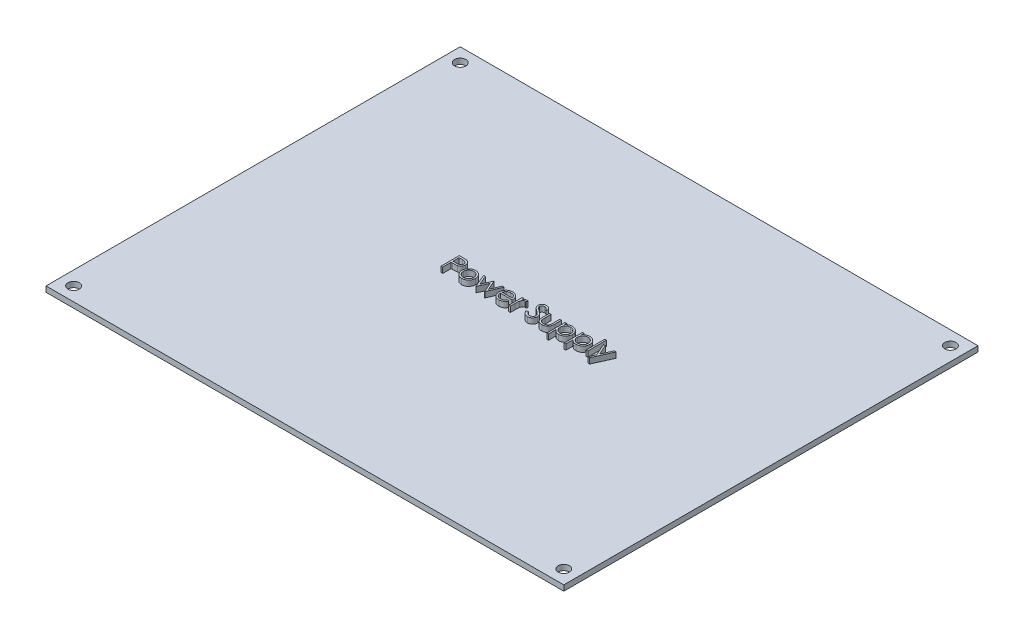
SolidWorks part; units mm, degrees
ref_plane "Front Plane" through (0, 0, 0) normal (0, 0, 1) x (1, 0, 0)
ref_plane "Top Plane" through (0, 0, 0) normal (0, 1, 0) x (1, 0, 0)
ref_plane "Right Plane" through (0, 0, 0) normal (1, 0, 0) x (0, 0, -1)
sketch "Sketch1" plane through (0, 0, 0) normal (0, 1, 0) x (1, 0, 0)
  line L1 (75, -60) -> (-75, -60)
  line L2 (75, -60) -> (75, 60)
  line L3 (75, 60) -> (-75, 60)
  line L4 (-75, -60) -> (-75, 60)
  line L5 (75, -60) -> (-75, 60) construction
  line L6 (75, 60) -> (-75, -60) construction
  point P0 (0, 0)
  dimension "D1" = 120
  dimension "D2" = 150
extrude "Boss-Extrude1" add sketch "Sketch1" along normal blind 1.6
hole_wizard "#4 Clearance Hole2" positions "Sketch4" profile "Sketch5" hole size "#4" standard "ANSI Inch" end condition through all
sketch "Sketch4" plane through (0, 1.6, 0) normal (0, 1, 0) x (1, 0, 0)
  line L0 (75, 60) -> (-75, 60) construction
  line L1 (-75, 60) -> (-75, -60) construction
  line L2 (75, -60) -> (75, 60) construction
  line L3 (-75, -60) -> (75, -60) construction
  point P0 (-71, 56)
  point P2 (71, 56)
  point P4 (71, -56)
  point P6 (-71, -56)
  point P19 (70.9175, 58.4005)
  point P20 (0, 0)
  point P21 (0, 0)
  dimension "D1" = 4
  dimension "D2" = 4
  dimension "D3" = 4
  dimension "D4" = 4
  dimension "D5" = 4
  dimension "D6" = 4
  dimension "D7" = 4
  dimension "D8" = 4
sketch "Sketch5" plane through (-71, 1.6, -56) normal (1, 0, 0) x (0, 0, 1)
  line L0 (0, 0) -> (0, 1.6)
  line L1 (0, 1.6) -> (1.6319, 1.6)
  line L2 (1.6319, 1.6) -> (1.6319, 0)
  line L5 (1.6319, 0) -> (0, 0)
  line L11 (0, -6.35) -> (0, 107.95) construction
  dimension "Thru Hole Dia." = 3.2639
  dimension "Thru Hole Depth" = 1.6
sketch "Sketch6" plane through (0, 1.6, 0) normal (0, 1, 0) x (1, 0, 0)
  text T0 "Power Supply" font "Century Gothic" height in points 20
extrude "Boss-Extrude2" add sketch "Sketch6" along normal blind 1.6
